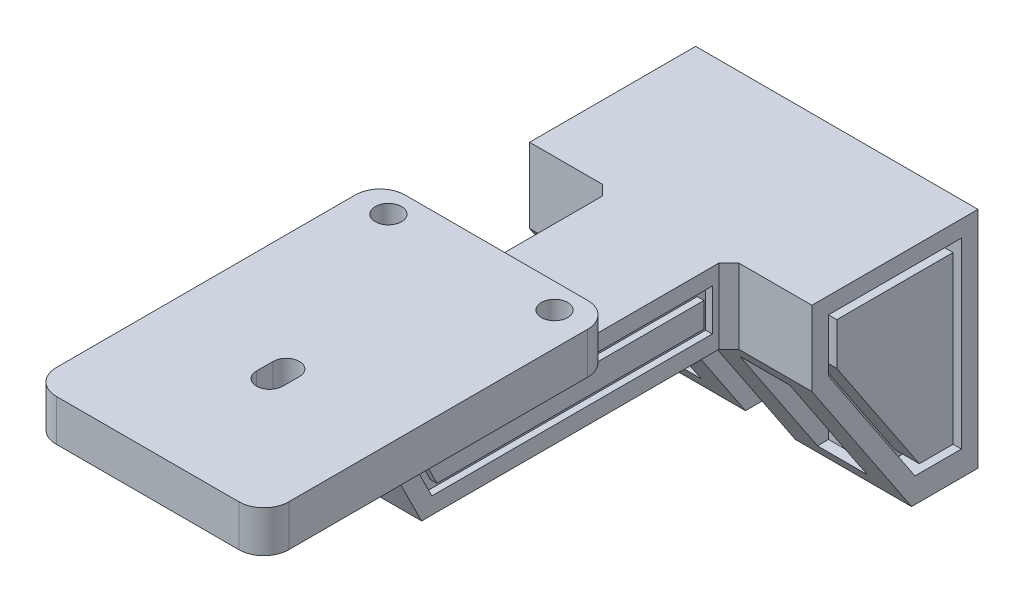
SolidWorks part; units mm, degrees
ref_plane "Front Plane" through (0, 0, 0) normal (0, 0, 1) x (1, 0, 0)
ref_plane "Top Plane" through (0, 0, 0) normal (0, 1, 0) x (1, 0, 0)
ref_plane "Right Plane" through (0, 0, 0) normal (1, 0, 0) x (0, 0, -1)
sketch "Sketch1" plane through (0, 0, 0) normal (0, 1, 0) x (1, 0, 0)
  line L0 (-14, -21) -> (-14, 21)
  line L1 (-14, 21) -> (14, 21)
  line L2 (14, 21) -> (14, -21)
  line L3 (-14, -21) -> (14, -21)
  dimension "D1" = 42
  dimension "D2" = 28
  dimension "D3" = 14
  dimension "D4" = 21
extrude "Boss-Extrude1" add sketch "Sketch1" along normal blind 5
fillet "Fillet1" radius 3 4 edges at (-14, 2.5, -21) (14, 2.5, -21) (14, 2.5, 21) (-14, 2.5, 21)
sketch "Sketch3" plane through (0, 5, 0) normal (0, 1, 0) x (1, 0, 0)
  line L0 (-14, 18) -> (-14, -18) construction
  line L1 (11, 21) -> (-11, 21) construction
  line L2 (1.585, -4.3) -> (1.585, -6.3)
  line L3 (-1.585, -4.3) -> (-1.585, -6.3)
  circle A0 centre (10, 18) radius 1.585
  circle A1 centre (-10, 18) radius 1.585
  arc A3 (1.585, -4.3) -> (-1.585, -4.3) centre (0, -4.3) ccw
  arc A4 (-1.585, -6.3) -> (1.585, -6.3) centre (0, -6.3) ccw
  dimension "D5" = 3.17
  dimension "D6" = 3.17
  dimension "D1" = 20
  dimension "D2" = 4
  dimension "D3" = 3
  dimension "D4" = 22.3
  dimension "D7" = 2
extrude "Cut-Extrude1" cut sketch "Sketch3" against normal blind 5
sketch "Sketch4" plane through (0, 0, 0) normal (0, -1, 0) x (1, 0, 0)
  line L1 (7, 1) -> (7, -62)
  line L2 (7, -62) -> (-7, -62)
  line L3 (-7, -62) -> (-7, 1)
  line L4 (-7, 1) -> (7, 1)
  line L5 (11, -21) -> (-11, -21) construction
  dimension "D1" = 7
  dimension "D2" = 7
  dimension "D3" = 1
  dimension "D4" = 41
extrude "Boss-Extrude2" add sketch "Sketch4" along normal blind 12
sketch "Sketch5" plane through (0, 0, 0) normal (0, 1, 0) x (1, 0, 0)
  line L0 (-7, 21) -> (7, 21)
  line L1 (7, 21) -> (7, 62)
  line L2 (7, 62) -> (-7, 62)
  line L3 (-7, 62) -> (-7, 21)
extrude "Cut-Extrude2" cut sketch "Sketch5" against normal blind 3
sketch "Sketch6" plane through (0, -12, 0) normal (0, -1, 0) x (1, 0, 0)
  line L0 (7, -62) -> (7, 1) construction
  line L1 (-3, -62) -> (-7, -62)
  line L2 (-3, -62) -> (-3, -54)
  line L3 (-3, -54) -> (-7, -54)
  line L4 (-7, -62) -> (-7, -54)
  line L5 (-3, -62) -> (-7, -54) construction
  line L6 (-3, -54) -> (-7, -62) construction
  line L7 (7, -62) -> (3, -62)
  line L8 (7, -62) -> (7, -54)
  line L9 (7, -54) -> (3, -54)
  line L10 (3, -62) -> (3, -54)
  line L11 (7, -62) -> (3, -54) construction
  line L12 (7, -54) -> (3, -62) construction
  line L13 (-7, 1) -> (-7, -62) construction
  line L14 (-7, -62) -> (7, -62) construction
  point P0 (-5, -58)
  point P5 (5, -58)
  dimension "D1" = 4
  dimension "D2" = 4
  dimension "D3" = 8
  dimension "D4" = 8
extrude "Boss-Extrude3" add sketch "Sketch6" along normal blind 18
sketch "Sketch7" plane through (-7, 0, 0) normal (-1, 0, 0) x (0, 0, 1)
  line L0 (-54, -30) -> (-54, -12) construction
  line L1 (-54, -30) -> (-62, -30)
  line L2 (-54, -30) -> (-54, -3)
  line L3 (-54, -3) -> (-62, -3)
  line L4 (-62, -30) -> (-62, -3)
  line L5 (-54, -30) -> (-62, -3) construction
  line L6 (-54, -3) -> (-62, -30) construction
  line L7 (-62, -30) -> (-62, -3) construction
  line L8 (-54, -30) -> (-62, -30) construction
  line L9 (-62, -3) -> (-21, -3) construction
  point P0 (-58, -16.5)
extrude "Boss-Extrude4" add sketch "Sketch7" along normal blind 10
sketch "Sketch8" plane through (7, 0, 0) normal (1, 0, 0) x (0, 0, -1)
  line L0 (21, -3) -> (62, -3) construction
  line L1 (62, -30) -> (54, -30)
  line L2 (62, -30) -> (62, -3)
  line L3 (62, -3) -> (54, -3)
  line L4 (54, -30) -> (54, -3)
  line L5 (62, -30) -> (54, -3) construction
  line L6 (62, -3) -> (54, -30) construction
  line L7 (54, -30) -> (54, -12) construction
  line L8 (62, -30) -> (62, -3) construction
  line L9 (62, -30) -> (54, -30) construction
  point P0 (58, -16.5)
extrude "Boss-Extrude5" add sketch "Sketch8" along normal blind 10
sketch "Sketch9" plane through (-7, 0, 0) normal (-1, 0, 0) x (0, 0, 1)
  line L1 (-54, -30) -> (-42, -12)
  line L2 (1, -12) -> (-54, -12) construction
  line L3 (-42, -12) -> (-42, -3)
  line L4 (-54, -3) -> (-21, -3) construction
  line L5 (-42, -3) -> (-54, -3)
  line L7 (-54, -3) -> (-54, -30)
  dimension "D1" = 12
extrude "Boss-Extrude6" add sketch "Sketch9" along normal blind 10 and the other way blind 4
sketch "Sketch10" plane through (7, 0, 0) normal (1, 0, 0) x (0, 0, -1)
  line L0 (42, -12) -> (42, -3)
  line L1 (21, -3) -> (54, -3) construction
  line L2 (42, -3) -> (54, -3)
  line L3 (54, -3) -> (54, -30)
  line L4 (54, -30) -> (42, -12)
extrude "Boss-Extrude7" add sketch "Sketch10" along normal blind 10 and the other way blind 4
sketch "Sketch13" plane through (-7, 0, 0) normal (-1, 0, 0) x (0, 0, 1)
  line L0 (1, 0) -> (-5, -12)
  line L1 (1, -12) -> (-42, -12) construction
  line L6 (-5, -12) -> (1, -12)
  line L7 (1, -12) -> (1, 0)
  dimension "D1" = 6
extrude "Cut-Extrude5" cut sketch "Sketch13" against normal blind 16
sketch "Sketch14" plane through (-7, 0, 0) normal (-1, 0, 0) x (0, 0, 1)
  line L0 (-21, 0) -> (-22.5, -3)
  line L1 (-42, -3) -> (-21, -3) construction
  line L2 (-22.5, -3) -> (-21, -3)
  line L3 (-21, -3) -> (-21, 0)
  line L4 (1, 0) -> (-5, -12) construction
extrude "Boss-Extrude8" add sketch "Sketch14" against normal blind 14
sketch "Sketch16" plane through (0, 0, -62) normal (0, 0, -1) x (-1, 0, 0)
  line L0 (-3, -30) -> (-3, -12) construction
  line L1 (3, -30) -> (3, -12) construction
  line L2 (-3, -30) -> (-17, -30) construction
  circle A0 centre (-10, -17) radius 2
  circle A1 centre (-10, -25) radius 2
  circle A2 centre (10, -17) radius 2
  circle A3 centre (10, -25) radius 2
  dimension "D1" = 4
  dimension "D2" = 7
  dimension "D3" = 7
  dimension "D4" = 8
  dimension "D5" = 5
extrude "Cut-Extrude6" cut sketch "Sketch16" against normal blind 27
sketch "Sketch19" plane through (0, 0, -62) normal (0, 0, -1) x (-1, 0, 0)
  line L0 (-13, -14) -> (-13, -28)
  line L1 (-13, -28) -> (-7, -28)
  line L2 (-7, -28) -> (-7, -14)
  line L3 (-7, -14) -> (-13, -14)
  line L4 (7, -14) -> (7, -28)
  line L5 (7, -28) -> (13, -28)
  line L6 (13, -28) -> (13, -14)
  line L7 (13, -14) -> (7, -14)
  line L8 (-17, -30) -> (-17, -3) construction
  line L9 (-3, -30) -> (-3, -12) construction
  line L10 (3, -30) -> (3, -12) construction
  line L11 (17, -3) -> (17, -30) construction
  line L12 (-17, -3) -> (17, -3) construction
  line L13 (17, -30) -> (3, -30) construction
  dimension "D1" = 4
  dimension "D2" = 4
  dimension "D3" = 4
  dimension "D4" = 4
  dimension "D5" = 11
  dimension "D6" = 2
extrude "Cut-Extrude8" cut sketch "Sketch19" against normal blind 14 from offset 8 offset against normal yes
sketch "Sketch20" plane through (-17, 0, 0) normal (-1, 0, 0) x (0, 0, 1)
  line L0 (-60, -5) -> (-60, -27)
  line L1 (-60, -27) -> (-54.4037, -27)
  line L2 (-54.4037, -27) -> (-44, -11.3944)
  line L3 (-44, -11.3944) -> (-44, -5)
  line L4 (-44, -5) -> (-60, -5)
  line L5 (-42, -3) -> (-62, -3) construction
  line L6 (-59, -6) -> (-59, -26)
  line L7 (-59, -26) -> (-54.9389, -26)
  line L8 (-54.9389, -26) -> (-45, -11.0917)
  line L9 (-45, -11.0917) -> (-45, -6)
  line L10 (-45, -6) -> (-59, -6)
  line L11 (-54, -30) -> (-42, -12) construction
  line L12 (-62, -3) -> (-62, -30) construction
  point P16 (-45, -8.5458)
  dimension "D1" = 1
  dimension "D2" = 1
  dimension "D3" = 1
  dimension "D4" = 1
  dimension "D5" = 2
  dimension "D6" = 16
  dimension "D7" = 2
  dimension "D8" = 22
  dimension "D9" = 1
  dimension "D10" = 2
extrude "Cut-Extrude9" cut sketch "Sketch20" against normal blind 1
sketch "Sketch24" plane through (-17, 0, 0) normal (-1, 0, 0) x (0, 0, 1)
  line L0 (-60, -5) -> (-60, -27)
  line L1 (-60, -27) -> (-54.4037, -27)
  line L2 (-54.4037, -27) -> (-44, -11.3944)
  line L3 (-44, -11.3944) -> (-44, -5)
  line L4 (-44, -5) -> (-60, -5)
  line L6 (-59, -6) -> (-59, -26)
  line L7 (-59, -26) -> (-54.9389, -26)
  line L8 (-54.9389, -26) -> (-45, -11.0917)
  line L9 (-45, -11.0917) -> (-45, -6)
  line L10 (-45, -6) -> (-59, -6)
  line L14 (-44, -5) -> (-60, -5) construction
  line L15 (-44, -11.3944) -> (-44, -5) construction
  line L16 (-54.9389, -26) -> (-45, -11.0917) construction
  point P16 (-45, -8.5458)
  dimension "D1" = 1
  dimension "D2" = 1
  dimension "D3" = 1
  dimension "D4" = 1
  dimension "D6" = 16
  dimension "D8" = 22
  dimension "D9" = 1
extrude "Cut-Extrude10" cut sketch "Sketch24" against normal blind 3 from offset 31 offset against normal yes
sketch "Sketch25" plane through (-7, 0, 0) normal (-1, 0, 0) x (0, 0, 1)
  line L0 (-40, -5) -> (-21.2639, -5)
  line L1 (-21.2639, -5) -> (-19.7639, -2)
  line L2 (-19.7639, -2) -> (-2.2361, -2)
  line L3 (-2.2361, -2) -> (-6.2361, -10)
  line L4 (-6.2361, -10) -> (-40, -10)
  line L5 (-40, -10) -> (-40, -5)
  line L6 (-39, -6) -> (-20.6459, -6)
  line L7 (-20.6459, -6) -> (-19.1459, -3)
  line L8 (-19.1459, -3) -> (-3.8541, -3)
  line L9 (-3.8541, -3) -> (-6.8541, -9)
  line L10 (-6.8541, -9) -> (-39, -9)
  line L11 (-39, -9) -> (-39, -6)
  line L12 (1, 0) -> (-5, -12) construction
  line L13 (-42, -3) -> (-22.5, -3) construction
  line L14 (-5, -12) -> (-42, -12) construction
  line L15 (-21, 0) -> (-22.5, -3) construction
  line L16 (1, 0) -> (-21, 0) construction
  line L17 (-42, -3) -> (-42, -12) construction
  point P10 (-40, -7.5)
  dimension "D1" = 1
  dimension "D2" = 1
  dimension "D3" = 1
  dimension "D4" = 1
  dimension "D5" = 1
  dimension "D6" = 1
  dimension "D7" = 2
  dimension "D8" = 2
  dimension "D9" = 2
  dimension "D10" = 2
  dimension "D11" = 2
  dimension "D12" = 2
extrude "Cut-Extrude11" cut sketch "Sketch25" against normal blind 0.8
sketch "Sketch26" plane through (-7, 0, 0) normal (-1, 0, 0) x (0, 0, 1)
  line L0 (-40, -5) -> (-21.2639, -5)
  line L1 (-21.2639, -5) -> (-19.7639, -2)
  line L2 (-19.7639, -2) -> (-2.2361, -2)
  line L3 (-2.2361, -2) -> (-6.2361, -10)
  line L4 (-6.2361, -10) -> (-40, -10)
  line L5 (-40, -10) -> (-40, -5)
  line L6 (-39, -6) -> (-20.6459, -6)
  line L7 (-20.6459, -6) -> (-19.1459, -3)
  line L8 (-19.1459, -3) -> (-3.8541, -3)
  line L9 (-3.8541, -3) -> (-6.8541, -9)
  line L10 (-6.8541, -9) -> (-39, -9)
  line L11 (-39, -9) -> (-39, -6)
  line L12 (-21.2639, -5) -> (-40, -5) construction
  line L18 (-6.2361, -10) -> (-2.2361, -2) construction
  line L19 (-19.1459, -3) -> (-20.6459, -6) construction
  line L20 (-2.2361, -2) -> (-19.7639, -2) construction
  line L21 (-40, -10) -> (-6.2361, -10) construction
  line L22 (-40, -5) -> (-40, -10) construction
  point P10 (-40, -7.5)
  dimension "D1" = 1
  dimension "D2" = 1
  dimension "D3" = 1
  dimension "D4" = 1
  dimension "D5" = 1
  dimension "D6" = 1
extrude "Cut-Extrude12" cut sketch "Sketch26" against normal blind 7.8 from offset 13.2 offset against normal yes
sketch "Sketch30" plane through (0, -12, 0) normal (0, -1, 0) x (1, 0, 0)
  line L0 (-7, -42) -> (-7, -40.8)
  line L1 (-7, -5) -> (-7, -42) construction
  line L2 (-7, -40.8) -> (-8.2, -42)
  line L3 (-7, -42) -> (-17, -42) construction
  line L4 (-8.2, -42) -> (-7, -42)
  line L5 (7, -42) -> (7, -40.8)
  line L6 (7, -42) -> (7, -5) construction
  line L7 (7, -40.8) -> (8.2, -42)
  line L8 (7, -42) -> (17, -42) construction
  line L9 (8.2, -42) -> (7, -42)
  dimension "D1" = 1.2
extrude "Boss-Extrude10" add sketch "Sketch30" against normal blind 9
